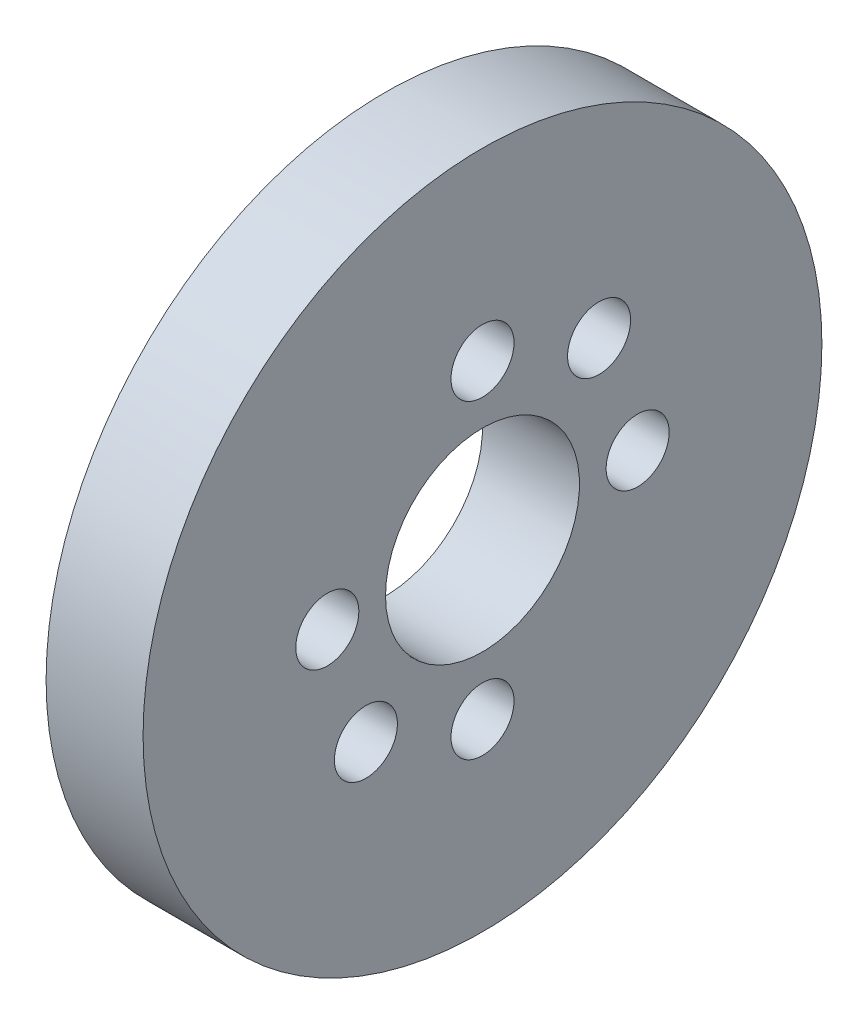
SolidWorks part; units mm, degrees
ref_plane "Front Plane" through (0, 0, 0) normal (0, 0, 1) x (1, 0, 0)
ref_plane "Top Plane" through (0, 0, 0) normal (0, 1, 0) x (1, 0, 0)
ref_plane "Right Plane" through (0, 0, 0) normal (1, 0, 0) x (0, 0, -1)
sketch "Sketch1" plane through (0, 0, 0) normal (0, 0, 1) x (1, 0, 0)
  line L0 (0, 0) -> (10, 0) construction
  line L1 (0, 10) -> (0, 35)
  line L2 (0, 40) -> (10, 40) construction
  line L3 (10, 35) -> (10, 10)
  line L4 (10, 10) -> (0, 10)
  line L5 (0, 40) -> (0, 35) construction
  line L6 (0, 35) -> (10, 35)
  line L7 (10, 40) -> (10, 35) construction
  dimension "D_s" = 20
  dimension "L" = 10
  dimension "T" = 5
  dimension "D" = 80
revolve "Revolve1" add sketch "Sketch1" angle 360 about L0
hole_wizard "Diameter Hole1" positions "Sketch3" profile "Sketch2" hole size "Ø4.5" standard "JIS" end condition through all
sketch "Sketch3" plane through (10, 0, 0) normal (1, 0, 0) x (0, 0, -1)
  circle A0 centre (0, 0) radius 16 construction
  point P5 (0, 16)
  point P7 (16, 0)
  point P9 (0, -16)
  point P11 (-16, 0)
  dimension "P" = 32
sketch "Sketch2" plane through (10, 0, 16) normal (0, 1, 0) x (0, 0, -1)
  line L0 (0, 0) -> (0, 10)
  line L1 (0, 10) -> (3.25, 10)
  line L2 (3.25, 10) -> (3.25, 0)
  line L5 (3.25, 0) -> (0, 0)
  line L11 (0, 0) -> (0, 10) construction
  dimension "S" = 6.5
  dimension "Thru Hole Depth" = 10
hole_wizard "Diameter Hole2" positions "Sketch5" profile "Sketch4" hole size "Ø5.5" standard "JIS" end condition through all
sketch "Sketch5" plane through (10, 0, 0) normal (1, 0, 0) x (0, 0, -1)
  line L0 (0, 0) -> (17, 0) construction
  line L2 (0, 0) -> (12.0208, 12.0208) construction
  circle A1 centre (0, 0) radius 17 construction
  point P21 (12.0208, 12.0208)
  point P25 (-12.0208, -12.0208)
  dimension "D1" = 45
  dimension "P2" = 34
sketch "Sketch4" plane through (10, -12.0208, 12.0208) normal (0, 1, 0) x (0, 0, -1)
  line L0 (0, 0) -> (0, 10)
  line L1 (0, 10) -> (3.25, 10)
  line L2 (3.25, 10) -> (3.25, 0)
  line L5 (3.25, 0) -> (0, 0)
  line L11 (0, 0) -> (0, 10) construction
  dimension "S2" = 6.5
  dimension "Thru Hole Depth" = 10
other "DeleteFace1" [suppressed]
hole_wizard "Tapped Hole1" [suppressed] positions "Sketch7" profile "Sketch6" tap size "M4x0.7" standard "JIS"
sketch "Sketch7" [suppressed] plane through (8, 0, 0) normal (1, 0, 0) x (0, 0, -1)
  circle A0 centre (0, 0) radius 9 construction
  point P5 (0, 9)
  point P7 (9, 0)
  point P9 (0, -9)
  point P11 (-9, 0)
  dimension "P" = 32
sketch "Sketch6" [suppressed] plane through (8, 9, 0) normal (0, 1, 0) x (0, 0, -1)
  line L0 (0, 0) -> (0, 8)
  line L1 (0, 8) -> (1.65, 8)
  line L2 (1.65, 8) -> (1.65, 0)
  line L5 (1.65, 0) -> (0, 0)
  line L11 (0, 0) -> (0, 8) construction
  dimension "Thru Tap Drill Dia." = 3.3
  dimension "Thru Tap Drill Depth" = 8
cosmetic thread "Hole Thread1" [suppressed] parameters "M"=4
cosmetic thread "Hole Thread2" [suppressed] parameters "M"=4
cosmetic thread "Hole Thread3" [suppressed] parameters "M"=4
cosmetic thread "Hole Thread4" [suppressed] parameters "M"=4
